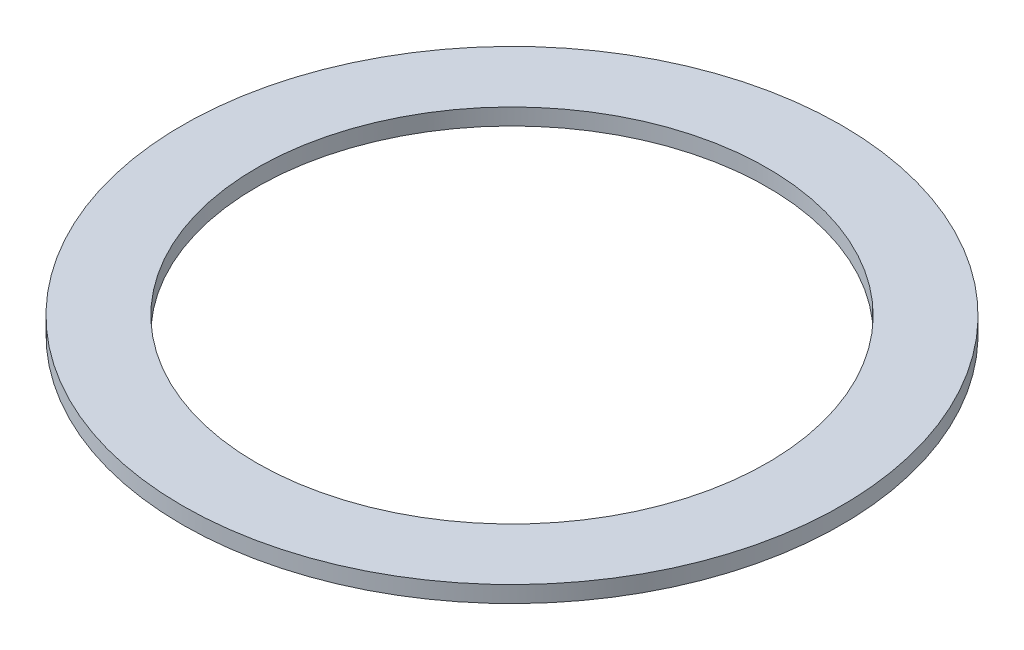
SolidWorks part; units mm, degrees
material "C40 or 38NiCrMo4"
ref_plane "Piano frontale" through (0, 0, 0) normal (0, 0, 1) x (1, 0, 0)
ref_plane "Piano superiore" through (0, 0, 0) normal (0, 1, 0) x (1, 0, 0)
ref_plane "Piano destro" through (0, 0, 0) normal (1, 0, 0) x (0, 0, -1)
sketch "Schizzo1" plane through (0, 0, 0) normal (0, 1, 0) x (1, 0, 0)
  circle A0 centre (0, 0) radius 31
  circle A1 centre (0, 0) radius 40
extrude "Estrusione1" add sketch "Schizzo1" along normal blind 2
